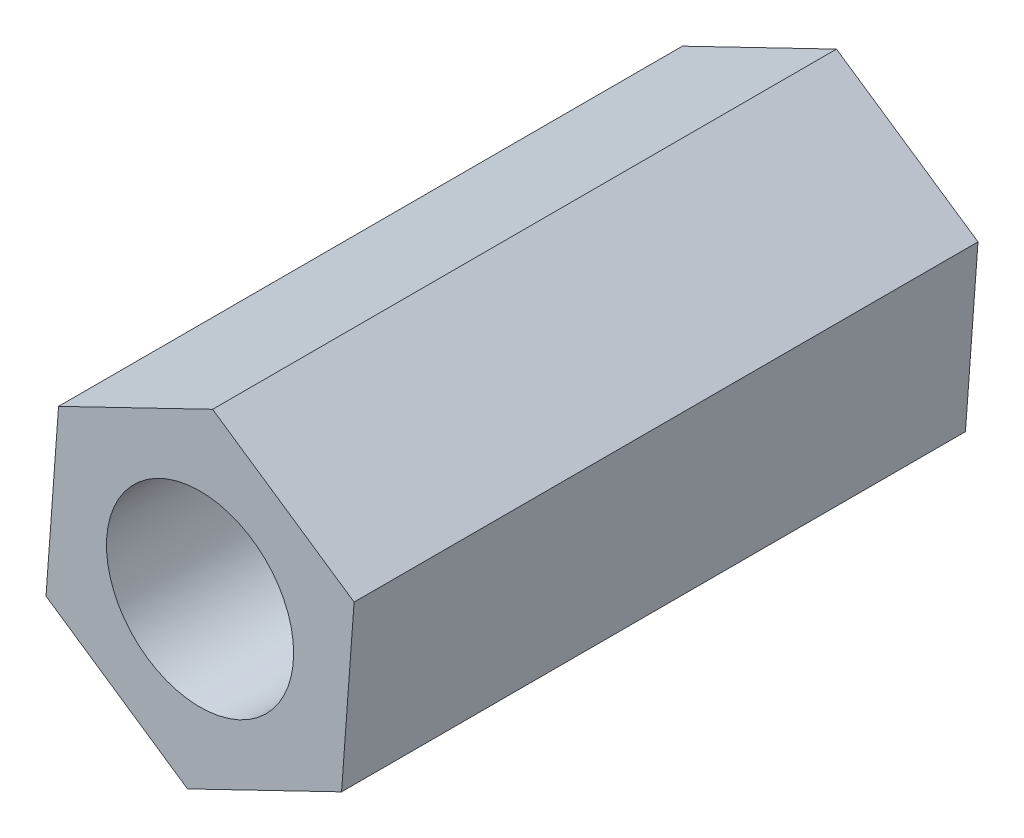
SolidWorks part; units mm, degrees
material "Alloy Steel"
ref_plane "정면" through (0, 0, 0) normal (0, 0, 1) x (1, 0, 0)
ref_plane "윗면" through (0, 0, 0) normal (0, 1, 0) x (1, 0, 0)
ref_plane "우측면" through (0, 0, 0) normal (1, 0, 0) x (0, 0, -1)
sketch "스케치3" plane through (0, 0, 0) normal (0, 0, 1) x (1, 0, 0)
  line L1 (9.0724, -6.1664) -> (9.8765, 4.7737)
  line L2 (9.8765, 4.7737) -> (0.8041, 10.9401)
  line L3 (0.8041, 10.9401) -> (-9.0724, 6.1664)
  line L4 (-9.0724, 6.1664) -> (-9.8765, -4.7737)
  line L5 (-9.8765, -4.7737) -> (-0.8041, -10.9401)
  line L6 (-0.8041, -10.9401) -> (9.0724, -6.1664)
  circle A0 centre (0, 0) radius 9.5 construction
  point P1 (5.3403, 7.8569)
  dimension "D1" = 9.5
extrude "보스-돌출1" add sketch "스케치3" against normal blind 40
sketch "스케치4" plane through (0, 0, 0) normal (0, 0, 1) x (1, 0, 0)
  circle A0 centre (0, 0) radius 6
  dimension "D1" = 12
extrude "컷-돌출1" cut sketch "스케치4" against normal through all
